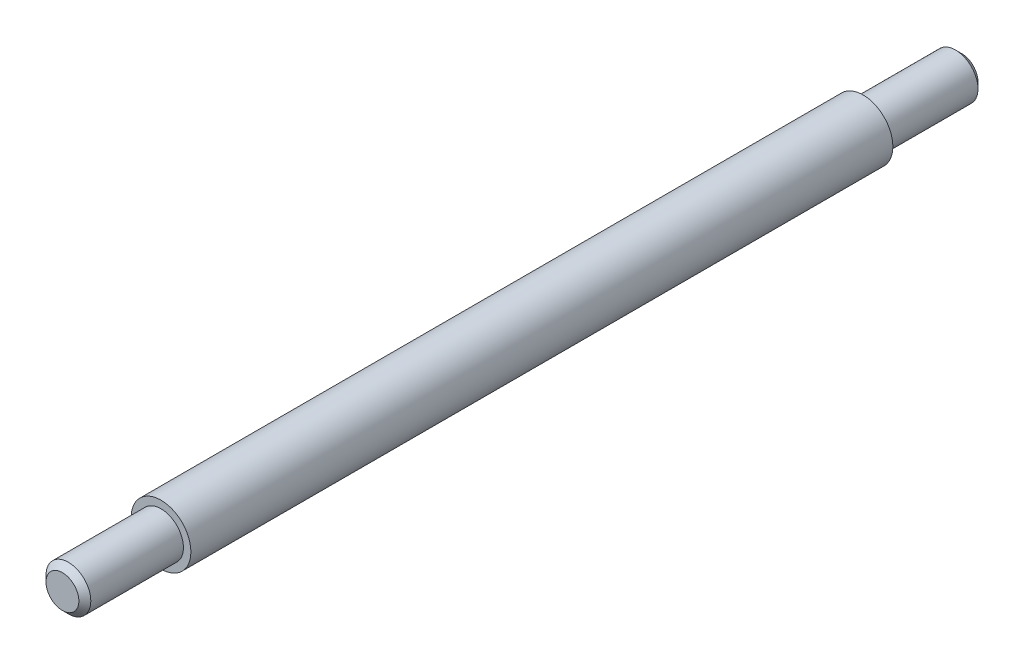
SolidWorks part; units mm, degrees
material "Chrome Stainless Steel"
ref_plane "Front Plane" through (0, 0, 0) normal (0, 0, 1) x (1, 0, 0)
ref_plane "Top Plane" through (0, 0, 0) normal (0, 1, 0) x (1, 0, 0)
ref_plane "Right Plane" through (0, 0, 0) normal (1, 0, 0) x (0, 0, -1)
sketch "Sketch1" plane through (0, 0, 0) normal (0, 0, 1) x (1, 0, 0)
  circle A0 centre (0, 0) radius 2
  dimension "D1" = 4
extrude "Boss-Extrude1" add sketch "Sketch1" against normal blind 47
sketch "Sketch2" plane through (0, 0, 0) normal (0, 0, 1) x (1, 0, 0)
  circle A0 centre (0, 0) radius 1.5
  dimension "D1" = 3
extrude "Boss-Extrude2" add sketch "Sketch2" along normal blind 6.6
sketch "Sketch3" plane through (0, 0, -47) normal (0, 0, -1) x (-1, 0, 0)
  circle A0 centre (0, 0) radius 1.5
  circle A1 centre (0, 0) radius 1.5 construction
extrude "Boss-Extrude3" add sketch "Sketch3" along normal blind 6.6
chamfer "Chamfer1" distance 0.4 angle 45 2 edges at (1.5, 0, 6.6) (-1.5, 0, -53.6)
